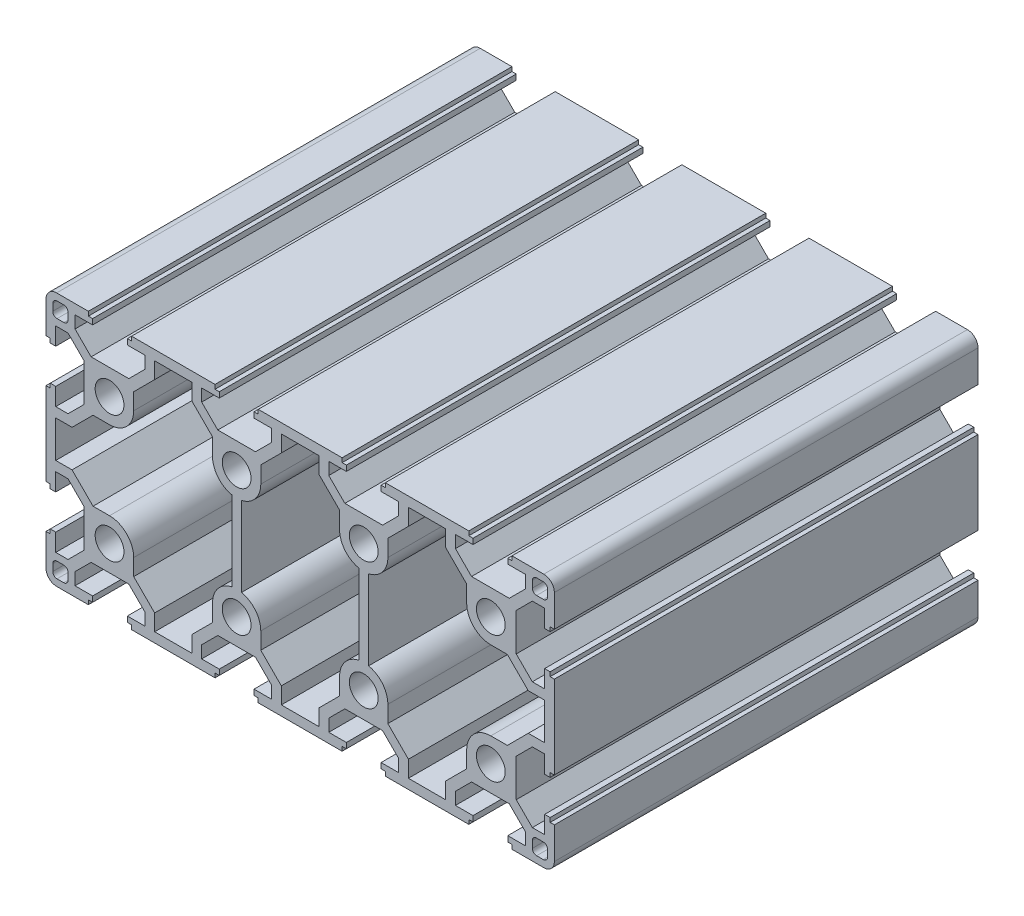
SolidWorks part; units mm, degrees
ref_plane "前视基准面" through (0, 0, 0) normal (0, 0, 1) x (1, 0, 0)
ref_plane "上视基准面" through (0, 0, 0) normal (0, 1, 0) x (1, 0, 0)
ref_plane "右视基准面" through (0, 0, 0) normal (1, 0, 0) x (0, 0, -1)
sketch "草图1" plane through (0, 0, 0) normal (0, 0, 1) x (1, 0, 0)
  line B0 (-10.8, 39.8) -> (-12.4, 39.8)
  line B1 (-13.4, 40.8) -> (-13.4, 42.4)
  line B2 (-12.4, 43.4) -> (-10.8, 43.4)
  line B3 (-9.8, 42.4) -> (-9.8, 40.8)
  line B4 (-9.8, -10.8) -> (-9.8, -12.4)
  line B5 (-10.8, -13.4) -> (-12.4, -13.4)
  line B6 (-13.4, -12.4) -> (-13.4, -10.8)
  line B7 (-12.4, -9.8) -> (-10.8, -9.8)
  line B8 (-3.8973, 5.7) -> (-8.8473, 10.65)
  line B9 (-8.8473, 10.65) -> (-12.7, 10.65)
  line B10 (-12.7, 10.65) -> (-12.7, 19.35)
  line B11 (-12.7, 19.35) -> (-8.8473, 19.35)
  line B12 (-8.8473, 19.35) -> (-3.8973, 24.3)
  line B13 (-3.8973, 24.3) -> (0, 24.3)
  line B14 (5.7, 30) -> (5.7, 33.8973)
  line B15 (5.7, 33.8973) -> (10.65, 38.8473)
  line B16 (10.65, 38.8473) -> (10.65, 42.7)
  line B17 (10.65, 42.7) -> (19.45, 42.7)
  line B18 (19.45, 42.7) -> (19.45, 38.8473)
  line B19 (19.45, 38.8473) -> (24.3, 33.9973)
  line B20 (24.3, 33.9973) -> (24.3, 30)
  line B21 (28.85, 24.4172) -> (28.85, 5.5828)
  line B22 (24.3, 0) -> (24.3, -3.9973)
  line B23 (24.3, -3.9973) -> (19.45, -8.8473)
  line B24 (19.45, -8.8473) -> (19.45, -12.7)
  line B25 (19.45, -12.7) -> (10.65, -12.7)
  line B26 (10.65, -12.7) -> (10.65, -8.8473)
  line B27 (10.65, -8.8473) -> (5.7, -3.8973)
  line B28 (5.7, -3.8973) -> (5.7, 0)
  line B29 (0, 5.7) -> (-3.8973, 5.7)
  line B30 (35.7, -3.95) -> (35.7, 0)
  line B31 (31.15, 5.5828) -> (31.15, 24.4172)
  line B32 (35.7, 30) -> (35.7, 33.95)
  line B33 (35.7, 33.95) -> (40.55, 38.8)
  line B34 (40.55, 38.8) -> (40.55, 42.7)
  line B35 (40.55, 42.7) -> (49.45, 42.7)
  line B36 (49.45, 42.7) -> (49.45, 38.8473)
  line B37 (49.45, 38.8473) -> (54.3, 33.9973)
  line B38 (54.3, 33.9973) -> (54.3, 30)
  line B39 (58.85, 24.4172) -> (58.85, 5.5828)
  line B40 (54.3, 0) -> (54.3, -3.9973)
  line B41 (54.3, -3.9973) -> (49.45, -8.8473)
  line B42 (49.45, -8.8473) -> (49.45, -12.7)
  line B43 (49.45, -12.7) -> (40.55, -12.7)
  line B44 (40.55, -12.7) -> (40.55, -8.8)
  line B45 (40.55, -8.8) -> (35.7, -3.95)
  line B46 (100.8, -9.8) -> (102.4, -9.8)
  line B47 (103.4, -10.8) -> (103.4, -12.4)
  line B48 (102.4, -13.4) -> (100.8, -13.4)
  line B49 (99.8, -12.4) -> (99.8, -10.8)
  line B50 (84.3, 0) -> (84.3, -3.8973)
  line B51 (84.3, -3.8973) -> (79.35, -8.8473)
  line B52 (79.35, -8.8473) -> (79.35, -12.7)
  line B53 (79.35, -12.7) -> (70.55, -12.7)
  line B54 (70.55, -12.7) -> (70.55, -8.8)
  line B55 (70.55, -8.8) -> (65.7, -3.95)
  line B56 (65.7, -3.95) -> (65.7, 0)
  line B57 (61.15, 5.5828) -> (61.15, 24.4172)
  line B58 (65.7, 30) -> (65.7, 33.95)
  line B59 (65.7, 33.95) -> (70.55, 38.8)
  line B60 (70.55, 38.8) -> (70.55, 42.7)
  line B61 (70.55, 42.7) -> (79.35, 42.7)
  line B62 (79.35, 42.7) -> (79.35, 38.8473)
  line B63 (79.35, 38.8473) -> (84.3, 33.8973)
  line B64 (84.3, 33.8973) -> (84.3, 30)
  line B65 (90, 24.3) -> (93.8973, 24.3)
  line B66 (93.8973, 24.3) -> (98.8473, 19.35)
  line B67 (98.8473, 19.35) -> (102.7, 19.35)
  line B68 (102.7, 19.35) -> (102.7, 10.65)
  line B69 (102.7, 10.65) -> (98.8473, 10.65)
  line B70 (98.8473, 10.65) -> (93.8973, 5.7)
  line B71 (93.8973, 5.7) -> (90, 5.7)
  line B72 (99.8, 40.8) -> (99.8, 42.4)
  line B73 (100.8, 43.4) -> (102.4, 43.4)
  line B74 (103.4, 42.4) -> (103.4, 40.8)
  line B75 (102.4, 39.8) -> (100.8, 39.8)
  line B76 (35.1, 45) -> (35.1, 44)
  line B77 (35.1, 44) -> (34.1, 44)
  line B78 (34.1, 44) -> (34.1, 42.7)
  line B79 (34.1, 42.7) -> (38.25, 42.7)
  line B80 (38.25, 42.7) -> (38.25, 39.8)
  line B81 (38.25, 39.8) -> (34.45, 36)
  line B82 (34.45, 36) -> (25.55, 36)
  line B83 (25.55, 36) -> (21.75, 39.8)
  line B84 (21.75, 39.8) -> (21.75, 42.7)
  line B85 (21.75, 42.7) -> (25.9, 42.7)
  line B86 (25.9, 42.7) -> (25.9, 44)
  line B87 (25.9, 44) -> (24.9, 44)
  line B88 (24.9, 44) -> (24.9, 45)
  line B89 (24.9, 45) -> (5.2, 45)
  line B90 (5.2, 45) -> (5.2, 44)
  line B91 (5.2, 44) -> (4.2, 44)
  line B92 (4.2, 44) -> (4.2, 42.7)
  line B93 (4.2, 42.7) -> (8.35, 42.7)
  line B94 (8.35, 42.7) -> (8.35, 39.8)
  line B95 (8.35, 39.8) -> (4.55, 36)
  line B96 (4.55, 36) -> (-4.35, 36)
  line B97 (-4.35, 36) -> (-8.15, 39.8)
  line B98 (-8.15, 39.8) -> (-8.15, 42.7)
  line B99 (-8.15, 42.7) -> (-4, 42.7)
  line B100 (-4, 42.7) -> (-4, 44)
  line B101 (-4, 44) -> (-5, 44)
  line B102 (-5, 44) -> (-5, 45)
  line B103 (-5, 45) -> (-12.5, 45)
  line B104 (-15, 42.5) -> (-15, 35)
  line B105 (-15, 35) -> (-14, 35)
  line B106 (-14, 35) -> (-14, 34)
  line B107 (-14, 34) -> (-12.7, 34)
  line B108 (-12.7, 34) -> (-12.7, 38.15)
  line B109 (-12.7, 38.15) -> (-9.8, 38.15)
  line B110 (-9.8, 38.15) -> (-6, 34.35)
  line B111 (-6, 34.35) -> (-6, 25.45)
  line B112 (-6, 25.45) -> (-9.8, 21.65)
  line B113 (-9.8, 21.65) -> (-12.7, 21.65)
  line B114 (-12.7, 21.65) -> (-12.7, 25.8)
  line B115 (-12.7, 25.8) -> (-14, 25.8)
  line B116 (-14, 25.8) -> (-14, 24.8)
  line B117 (-14, 24.8) -> (-15, 24.8)
  line B118 (-15, 24.8) -> (-15, 5.2)
  line B119 (-15, 5.2) -> (-14, 5.2)
  line B120 (-14, 5.2) -> (-14, 4.2)
  line B121 (-14, 4.2) -> (-12.7, 4.2)
  line B122 (-12.7, 4.2) -> (-12.7, 8.35)
  line B123 (-12.7, 8.35) -> (-9.8, 8.35)
  line B124 (-9.8, 8.35) -> (-6, 4.55)
  line B125 (-6, 4.55) -> (-6, -4.35)
  line B126 (-6, -4.35) -> (-9.8, -8.15)
  line B127 (-9.8, -8.15) -> (-12.7, -8.15)
  line B128 (-12.7, -8.15) -> (-12.7, -4)
  line B129 (-12.7, -4) -> (-14, -4)
  line B130 (-14, -4) -> (-14, -5)
  line B131 (-14, -5) -> (-15, -5)
  line B132 (-15, -5) -> (-15, -12.5)
  line B133 (-12.5, -15) -> (-5, -15)
  line B134 (-5, -15) -> (-5, -14)
  line B135 (-5, -14) -> (-4, -14)
  line B136 (-4, -14) -> (-4, -12.7)
  line B137 (-4, -12.7) -> (-8.15, -12.7)
  line B138 (-8.15, -12.7) -> (-8.15, -9.8)
  line B139 (-8.15, -9.8) -> (-4.35, -6)
  line B140 (-4.35, -6) -> (4.55, -6)
  line B141 (4.55, -6) -> (8.35, -9.8)
  line B142 (8.35, -9.8) -> (8.35, -12.7)
  line B143 (8.35, -12.7) -> (4.2, -12.7)
  line B144 (4.2, -12.7) -> (4.2, -14)
  line B145 (4.2, -14) -> (5.2, -14)
  line B146 (5.2, -14) -> (5.2, -15)
  line B147 (5.2, -15) -> (24.9, -15)
  line B148 (24.9, -15) -> (24.9, -14)
  line B149 (24.9, -14) -> (25.9, -14)
  line B150 (25.9, -14) -> (25.9, -12.7)
  line B151 (25.9, -12.7) -> (21.75, -12.7)
  line B152 (21.75, -12.7) -> (21.75, -9.8)
  line B153 (21.75, -9.8) -> (25.55, -6)
  line B154 (25.55, -6) -> (34.45, -6)
  line B155 (34.45, -6) -> (38.25, -9.8)
  line B156 (38.25, -9.8) -> (38.25, -12.7)
  line B157 (38.25, -12.7) -> (34.1, -12.7)
  line B158 (34.1, -12.7) -> (34.1, -14)
  line B159 (34.1, -14) -> (35.1, -14)
  line B160 (35.1, -14) -> (35.1, -15)
  line B161 (35.1, -15) -> (54.9, -15)
  line B162 (54.9, -15) -> (54.9, -14)
  line B163 (54.9, -14) -> (55.9, -14)
  line B164 (55.9, -14) -> (55.9, -12.7)
  line B165 (55.9, -12.7) -> (51.75, -12.7)
  line B166 (51.75, -12.7) -> (51.75, -9.8)
  line B167 (51.75, -9.8) -> (55.55, -6)
  line B168 (55.55, -6) -> (64.45, -6)
  line B169 (64.45, -6) -> (68.25, -9.8)
  line B170 (68.25, -9.8) -> (68.25, -12.7)
  line B171 (68.25, -12.7) -> (64.1, -12.7)
  line B172 (64.1, -12.7) -> (64.1, -14)
  line B173 (64.1, -14) -> (65.1, -14)
  line B174 (65.1, -14) -> (65.1, -15)
  line B175 (65.1, -15) -> (84.8, -15)
  line B176 (84.8, -15) -> (84.8, -14)
  line B177 (84.8, -14) -> (85.8, -14)
  line B178 (85.8, -14) -> (85.8, -12.7)
  line B179 (85.8, -12.7) -> (81.65, -12.7)
  line B180 (81.65, -12.7) -> (81.65, -9.8)
  line B181 (81.65, -9.8) -> (85.45, -6)
  line B182 (85.45, -6) -> (94.35, -6)
  line B183 (94.35, -6) -> (98.15, -9.8)
  line B184 (98.15, -9.8) -> (98.15, -12.7)
  line B185 (98.15, -12.7) -> (94, -12.7)
  line B186 (94, -12.7) -> (94, -14)
  line B187 (94, -14) -> (95, -14)
  line B188 (95, -14) -> (95, -15)
  line B189 (95, -15) -> (102.5, -15)
  line B190 (105, -12.5) -> (105, -5)
  line B191 (105, -5) -> (104, -5)
  line B192 (104, -5) -> (104, -4)
  line B193 (104, -4) -> (102.7, -4)
  line B194 (102.7, -4) -> (102.7, -8.15)
  line B195 (102.7, -8.15) -> (99.8, -8.15)
  line B196 (99.8, -8.15) -> (96, -4.35)
  line B197 (96, -4.35) -> (96, 4.55)
  line B198 (96, 4.55) -> (99.8, 8.35)
  line B199 (99.8, 8.35) -> (102.7, 8.35)
  line B200 (102.7, 8.35) -> (102.7, 4.2)
  line B201 (102.7, 4.2) -> (104, 4.2)
  line B202 (104, 4.2) -> (104, 5.2)
  line B203 (104, 5.2) -> (105, 5.2)
  line B204 (105, 5.2) -> (105, 24.8)
  line B205 (105, 24.8) -> (104, 24.8)
  line B206 (104, 24.8) -> (104, 25.8)
  line B207 (104, 25.8) -> (102.7, 25.8)
  line B208 (102.7, 25.8) -> (102.7, 21.65)
  line B209 (102.7, 21.65) -> (99.8, 21.65)
  line B210 (99.8, 21.65) -> (96, 25.45)
  line B211 (96, 25.45) -> (96, 34.35)
  line B212 (96, 34.35) -> (99.8, 38.15)
  line B213 (99.8, 38.15) -> (102.7, 38.15)
  line B214 (102.7, 38.15) -> (102.7, 34)
  line B215 (102.7, 34) -> (104, 34)
  line B216 (104, 34) -> (104, 35)
  line B217 (104, 35) -> (105, 35)
  line B218 (105, 35) -> (105, 42.5)
  line B219 (102.5, 45) -> (95, 45)
  line B220 (95, 45) -> (95, 44)
  line B221 (95, 44) -> (94, 44)
  line B222 (94, 44) -> (94, 42.8)
  line B223 (94, 42.8) -> (98.15, 42.8)
  line B224 (98.15, 42.8) -> (98.15, 39.8)
  line B225 (98.15, 39.8) -> (94.35, 36)
  line B226 (94.35, 36) -> (85.45, 36)
  line B227 (85.45, 36) -> (81.65, 39.8)
  line B228 (81.65, 39.8) -> (81.65, 42.7)
  line B229 (81.65, 42.7) -> (85.8, 42.7)
  line B230 (85.8, 42.7) -> (85.8, 44)
  line B231 (85.8, 44) -> (84.8, 44)
  line B232 (84.8, 44) -> (84.8, 45)
  line B233 (84.8, 45) -> (65.1, 45)
  line B234 (65.1, 45) -> (65.1, 44)
  line B235 (65.1, 44) -> (64.1, 44)
  line B236 (64.1, 44) -> (64.1, 42.7)
  line B237 (64.1, 42.7) -> (68.25, 42.7)
  line B238 (68.25, 42.7) -> (68.25, 39.8)
  line B239 (68.25, 39.8) -> (64.45, 36)
  line B240 (64.45, 36) -> (55.55, 36)
  line B241 (55.55, 36) -> (51.75, 39.8)
  line B242 (51.75, 39.8) -> (51.75, 42.7)
  line B243 (51.75, 42.7) -> (55.9, 42.7)
  line B244 (55.9, 42.7) -> (55.9, 44)
  line B245 (55.9, 44) -> (54.9, 44)
  line B246 (54.9, 44) -> (54.9, 45)
  line B247 (54.9, 45) -> (35.1, 45)
  arc B248 (-10.8, 39.8) -> (-9.8, 40.8) centre (-10.8, 40.8) ccw
  arc B249 (-13.4, 40.8) -> (-12.4, 39.8) centre (-12.4, 40.8) ccw
  arc B250 (-12.4, 43.4) -> (-13.4, 42.4) centre (-12.4, 42.4) ccw
  arc B251 (-9.8, 42.4) -> (-10.8, 43.4) centre (-10.8, 42.4) ccw
  arc B252 (-9.8, -10.8) -> (-10.8, -9.8) centre (-10.8, -10.8) ccw
  arc B253 (-10.8, -13.4) -> (-9.8, -12.4) centre (-10.8, -12.4) ccw
  arc B254 (-13.4, -12.4) -> (-12.4, -13.4) centre (-12.4, -12.4) ccw
  arc B255 (-12.4, -9.8) -> (-13.4, -10.8) centre (-12.4, -10.8) ccw
  circle B256 centre (0, 30) radius 3.4
  circle B257 centre (0, 0) radius 3.4
  arc B258 (0, 24.3) -> (5.7, 30) centre (0, 30) ccw
  arc B259 (24.3, 30) -> (28.85, 24.4172) centre (30, 30) ccw
  arc B260 (28.85, 5.5828) -> (24.3, 0) centre (30, 0) ccw
  arc B261 (5.7, 0) -> (0, 5.7) centre (0, 0) ccw
  circle B262 centre (30, 0) radius 3.4
  circle B263 centre (30, 30) radius 3.4
  arc B264 (35.7, 0) -> (31.15, 5.5828) centre (30, 0) ccw
  arc B265 (31.15, 24.4172) -> (35.7, 30) centre (30, 30) ccw
  arc B266 (54.3, 30) -> (58.85, 24.4172) centre (60, 30) ccw
  arc B267 (58.85, 5.5828) -> (54.3, 0) centre (60, 0) ccw
  circle B268 centre (60, 30) radius 3.4
  circle B269 centre (60, 0) radius 3.4
  arc B270 (100.8, -9.8) -> (99.8, -10.8) centre (100.8, -10.8) ccw
  arc B271 (103.4, -10.8) -> (102.4, -9.8) centre (102.4, -10.8) ccw
  arc B272 (102.4, -13.4) -> (103.4, -12.4) centre (102.4, -12.4) ccw
  arc B273 (99.8, -12.4) -> (100.8, -13.4) centre (100.8, -12.4) ccw
  circle B274 centre (90, 0) radius 3.4
  arc B275 (90, 5.7) -> (84.3, 0) centre (90, 0) ccw
  arc B276 (65.7, 0) -> (61.15, 5.5828) centre (60, 0) ccw
  arc B277 (61.15, 24.4172) -> (65.7, 30) centre (60, 30) ccw
  arc B278 (84.3, 30) -> (90, 24.3) centre (90, 30) ccw
  circle B279 centre (90, 30) radius 3.4
  arc B280 (99.8, 40.8) -> (100.8, 39.8) centre (100.8, 40.8) ccw
  arc B281 (100.8, 43.4) -> (99.8, 42.4) centre (100.8, 42.4) ccw
  arc B282 (103.4, 42.4) -> (102.4, 43.4) centre (102.4, 42.4) ccw
  arc B283 (102.4, 39.8) -> (103.4, 40.8) centre (102.4, 40.8) ccw
  arc B284 (-12.5, 45) -> (-15, 42.5) centre (-12.5, 42.5) ccw
  arc B285 (-15, -12.5) -> (-12.5, -15) centre (-12.5, -12.5) ccw
  arc B286 (102.5, -15) -> (105, -12.5) centre (102.5, -12.5) ccw
  arc B287 (105, 42.5) -> (102.5, 45) centre (102.5, 42.5) ccw
sketch_block_instance "A$C76D21900-1"
sketch_block "A$C76D21900"
extrude "凸台-拉伸1" add sketch "草图1" along normal blind 100
